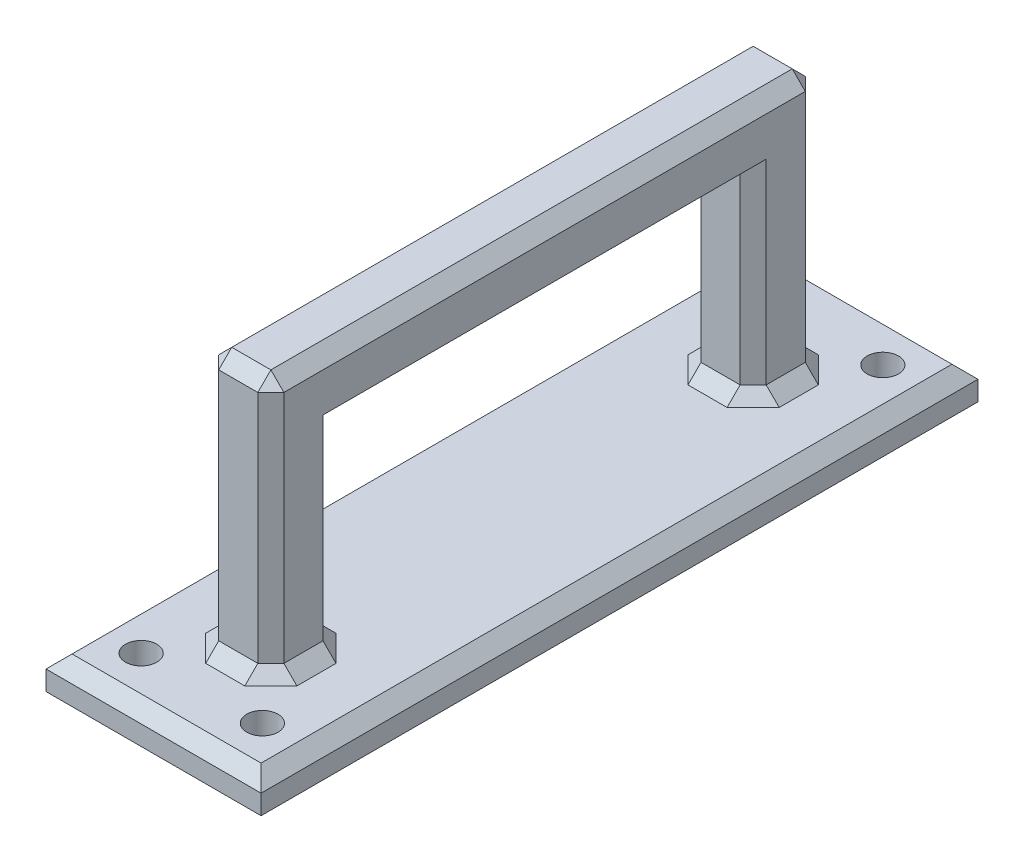
SolidWorks part; units mm, degrees
ref_plane "Front Plane" through (0, 0, 0) normal (0, 0, 1) x (1, 0, 0)
ref_plane "Top Plane" through (0, 0, 0) normal (0, 1, 0) x (1, 0, 0)
ref_plane "Right Plane" through (0, 0, 0) normal (1, 0, 0) x (0, 0, -1)
sketch "Sketch1" plane through (0, 0, 0) normal (0, 1, 0) x (1, 0, 0)
  line L1 (0, 0) -> (-41.91, 0)
  line L2 (0, 0) -> (0, 139.7)
  line L3 (0, 139.7) -> (-41.91, 139.7)
  line L4 (-41.91, 0) -> (-41.91, 139.7)
  dimension "D1" = 139.7
  dimension "D2" = 41.91
extrude "Boss-Extrude1" add sketch "Sketch1" along normal blind 6.35
sketch "Sketch2" plane through (0, 6.35, 0) normal (0, 1, 0) x (1, 0, 0)
  line L1 (-32.766, 130.302) -> (-9.144, 130.302) construction
  line L5 (-9.144, 130.302) -> (-9.144, 9.398) construction
  line L6 (-9.144, 9.398) -> (-32.766, 9.398) construction
  line L7 (-32.766, 9.398) -> (-32.766, 130.302) construction
  line L9 (-20.955, 130.302) -> (-20.955, 9.398) construction
  line L10 (-32.766, 69.85) -> (-9.144, 69.85) construction
  line L11 (0, 139.7) -> (-41.91, 139.7) construction
  line L12 (-41.91, 0) -> (0, 0) construction
  line L13 (0, 0) -> (0, 139.7) construction
  line L14 (-41.91, 139.7) -> (-41.91, 0) construction
  circle A0 centre (-32.766, 130.302) radius 3.048
  circle A1 centre (-9.144, 130.302) radius 3.048
  circle A2 centre (-9.144, 9.398) radius 3.048
  circle A3 centre (-32.766, 9.398) radius 3.048
  dimension "D3" = 6.096
  dimension "D1" = 23.622
  dimension "D2" = 120.904
extrude "Cut-Extrude1" cut sketch "Sketch2" against normal through all
sketch "Sketch3" plane through (0, 6.35, 0) normal (0, 1, 0) x (1, 0, 0)
  line L0 (-20.955, 139.7) -> (-20.955, 0) construction
  line L1 (-27.305, 123.19) -> (-14.605, 123.19)
  line L2 (-27.305, 123.19) -> (-27.305, 110.49)
  line L3 (-27.305, 110.49) -> (-14.605, 110.49)
  line L4 (-14.605, 123.19) -> (-14.605, 110.49)
  line L5 (-27.305, 29.21) -> (-14.605, 29.21)
  line L6 (-27.305, 29.21) -> (-27.305, 16.51)
  line L7 (-27.305, 16.51) -> (-14.605, 16.51)
  line L8 (-14.605, 29.21) -> (-14.605, 16.51)
  line L9 (0, 139.7) -> (-41.91, 139.7) construction
  line L10 (-41.91, 0) -> (0, 0) construction
  line L11 (-41.91, 69.85) -> (0, 69.85) construction
  line L12 (-41.91, 139.7) -> (-41.91, 0) construction
  line L13 (0, 0) -> (0, 139.7) construction
  dimension "D1" = 81.28
  dimension "D2" = 12.7
extrude "Boss-Extrude2" add sketch "Sketch3" along normal blind 50.8
sketch "Sketch4" plane through (0, 0, -110.49) normal (0, 0, 1) x (1, 0, 0)
  line L0 (-14.605, 57.15) -> (-14.605, 6.35) construction
  line L1 (-27.305, 57.15) -> (-14.605, 57.15)
  line L2 (-27.305, 57.15) -> (-27.305, 44.45)
  line L3 (-27.305, 44.45) -> (-14.605, 44.45)
  line L4 (-14.605, 57.15) -> (-14.605, 44.45)
extrude "Boss-Extrude3" add sketch "Sketch4" along normal up to next
chamfer "Chamfer1" distance 2.54 angle 45 26 edges at (-41.91, 6.35, -69.85) (-20.955, 6.35, -139.7) (-20.955, 6.35, 0) (0, 6.35, -69.85) (-14.605, 44.45, -69.85) (-27.305, 44.45, -69.85) (-27.305, 25.4, -110.49) (-14.605, 25.4, -29.21) (-27.305, 25.4, -29.21) (-14.605, 25.4, -110.49) (-14.605, 31.75, -16.51) (-14.605, 57.15, -69.85) (-14.605, 31.75, -123.19) (-20.955, 6.35, -123.19) (-14.605, 6.35, -116.84) (-20.955, 6.35, -110.49) (-27.305, 6.35, -116.84) (-27.305, 31.75, -123.19) (-20.955, 57.15, -123.19) (-27.305, 57.15, -69.85) (-20.955, 6.35, -16.51) (-20.955, 57.15, -16.51) (-27.305, 31.75, -16.51) (-27.305, 6.35, -22.86) (-20.955, 6.35, -29.21) (-14.605, 6.35, -22.86)
